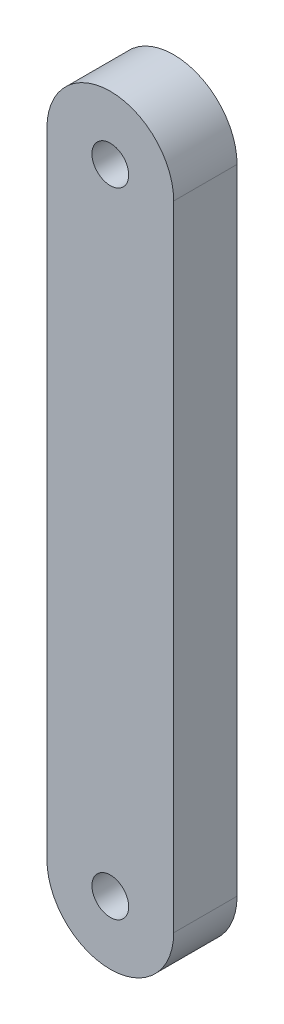
SolidWorks part; units mm, degrees
ref_plane "Front Plane" through (0, 0, 0) normal (0, 0, 1) x (1, 0, 0)
ref_plane "Top Plane" through (0, 0, 0) normal (0, 1, 0) x (1, 0, 0)
ref_plane "Right Plane" through (0, 0, 0) normal (1, 0, 0) x (0, 0, -1)
sketch "Sketch1" plane through (0, 0, 0) normal (0, 0, 1) x (1, 0, 0)
  line L0 (0, 25) -> (0, -25) construction
  line L1 (5, 25) -> (5, -25)
  line L2 (-5, 25) -> (-5, -25)
  arc A0 (5, 25) -> (-5, 25) centre (0, 25) ccw
  arc A1 (-5, -25) -> (5, -25) centre (0, -25) ccw
  point P3 (0, 0)
  dimension "D1" = 10
  dimension "D2" = 50
extrude "Boss-Extrude1" add sketch "Sketch1" along normal blind 5
hole_wizard "M2.5 Clearance Hole1" positions "Sketch2" profile "Sketch3" hole size "M2.5" standard "ANSI Metric" end condition through all
sketch "Sketch2" plane through (0, 0, 5) normal (0, 0, 1) x (1, 0, 0)
  arc A0 (-5, -25) -> (5, -25) centre (0, -25) ccw construction
  arc A1 (5, 25) -> (-5, 25) centre (0, 25) ccw construction
  point P0 (0, 25)
  point P2 (0, -25)
sketch "Sketch3" plane through (0, 25, 5) normal (1, 0, 0) x (0, -1, 0)
  line L0 (0, 0) -> (0, 5)
  line L1 (0, 5) -> (1.45, 5)
  line L2 (1.45, 5) -> (1.45, 0)
  line L5 (1.45, 0) -> (0, 0)
  line L11 (0, -6.35) -> (0, 107.95) construction
  dimension "Thru Hole Dia." = 2.9
  dimension "Thru Hole Depth" = 5
